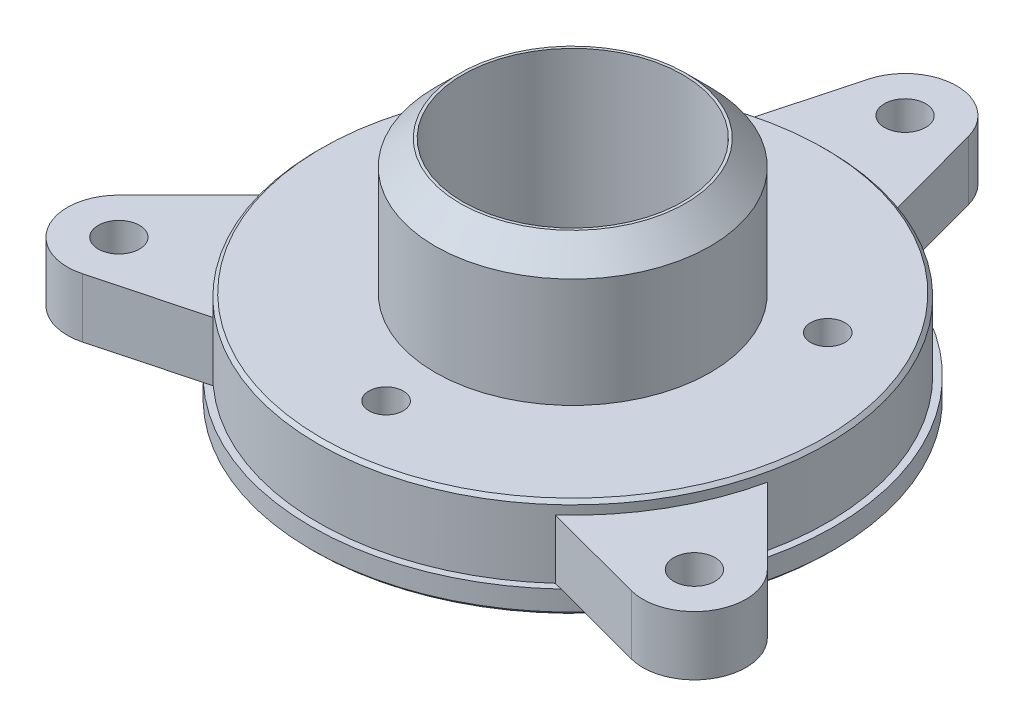
SolidWorks part; units mm, degrees
ref_plane "Front Plane" through (0, 0, 0) normal (0, 0, 1) x (1, 0, 0)
ref_plane "Top Plane" through (0, 0, 0) normal (0, 1, 0) x (1, 0, 0)
ref_plane "Right Plane" through (0, 0, 0) normal (1, 0, 0) x (0, 0, -1)
sketch "Sketch1" plane through (0, 0, 0) normal (0, 1, 0) x (1, 0, 0)
  line L0 (0, 0) -> (0, -18.5) construction
  line L1 (0, 0) -> (0, 24.15) construction
  line L2 (-3.6202, 25.1282) -> (-5.65, 17.6161)
  line L3 (3.6202, 25.1282) -> (5.65, 17.6161)
  line L4 (23.5717, -9.4289) -> (18.081, -3.915)
  line L5 (19.9516, -15.6993) -> (12.431, -13.7011)
  line L6 (-19.9516, -15.6993) -> (-12.431, -13.7011)
  line L7 (-23.5717, -9.4289) -> (-18.081, -3.915)
  arc A0 (-5.65, 17.6161) -> (-18.081, -3.915) centre (0, 0) ccw
  circle A1 centre (0, 4.7) radius 23.2 construction
  arc A2 (3.6202, 25.1282) -> (-3.6202, 25.1282) centre (0, 24.15) ccw
  circle A3 centre (0, 24.15) radius 1.5
  arc A4 (19.9516, -15.6993) -> (23.5717, -9.4289) centre (20.9145, -12.075) ccw
  circle A5 centre (20.9145, -12.075) radius 1.5
  arc A6 (-23.5717, -9.4289) -> (-19.9516, -15.6993) centre (-20.9145, -12.075) ccw
  circle A7 centre (-20.9145, -12.075) radius 1.5
  arc A8 (-12.431, -13.7011) -> (12.431, -13.7011) centre (0, 0) ccw
  arc A9 (18.081, -3.915) -> (5.65, 17.6161) centre (0, 0) ccw
  point P30 (0, 0)
  dimension "D1" = 37
  dimension "D3" = 7.5
  dimension "D4" = 5.65
  dimension "D5" = 3
  dimension "D2" = 23.2
  dimension "D6" = 3
extrude "Boss-Extrude1" add sketch "Sketch1" along normal blind 4.3
sketch "Sketch3" plane through (0, 4.3, 0) normal (0, 1, 0) x (1, 0, 0)
  circle A0 centre (0, 0) radius 18.5
extrude "Boss-Extrude2" add sketch "Sketch3" along normal blind 0.9
sketch "Sketch2" plane through (0, 4.3, 0) normal (0, 1, 0) x (1, 0, 0)
  line L0 (0, -13.5677) -> (-11.75, 6.7839) construction
  line L1 (-11.75, 6.7839) -> (11.75, 6.7839) construction
  line L2 (11.75, 6.7839) -> (0, -13.5677) construction
  circle A0 centre (0, 0) radius 13.5677 construction
  circle A1 centre (-11.75, 6.7839) radius 1.25
  circle A2 centre (11.75, 6.7839) radius 1.25
  circle A3 centre (0, -13.5677) radius 1.25
  dimension "D2" = 2.5
  dimension "D1" = 23.5
extrude "Cut-Extrude1" cut sketch "Sketch2" against normal through all and the other way through all
sketch "Sketch4" plane through (0, 5.2, 0) normal (0, 1, 0) x (1, 0, 0)
  circle A0 centre (0, 0) radius 10
  dimension "D1" = 20
extrude "Boss-Extrude3" add sketch "Sketch4" along normal blind 9.75
sketch "Sketch5" plane through (0, 14.95, 0) normal (0, 1, 0) x (1, 0, 0)
  circle A0 centre (0, 0) radius 8
  dimension "D1" = 16
extrude "Cut-Extrude2" cut sketch "Sketch5" against normal through all
sketch "Sketch6" plane through (0, 0, 0) normal (0, -1, 0) x (1, 0, 0)
  circle A0 centre (0, 0) radius 19
  dimension "D1" = 38
extrude "Boss-Extrude4" add sketch "Sketch6" along normal blind 1.7
sketch "Sketch7" plane through (0, -1.7, 0) normal (0, -1, 0) x (-1, 0, 0)
  circle A0 centre (0, 0) radius 17.5
  dimension "D1" = 35
extrude "Cut-Extrude3" cut sketch "Sketch7" against normal offset from surface (4.4 mm away) 2.5 up to face at (0, 5.2, 10)
chamfer "Chamfer1" distance 1.8 angle 45 1 edges at (0, 14.95, 10)
chamfer "Chamfer2" distance 0.25 angle 45 4 edges at (0, 2.7, 17.5) (0, -1.7, -17.5) (0, 5.2, 18.5) (0, -1.7, -19)
chamfer "Chamfer3" distance 0.5 angle 45 3 edges at (20.9145, 0, 13.575) (-20.9145, 0, 13.575) (0, 0, -22.65)
